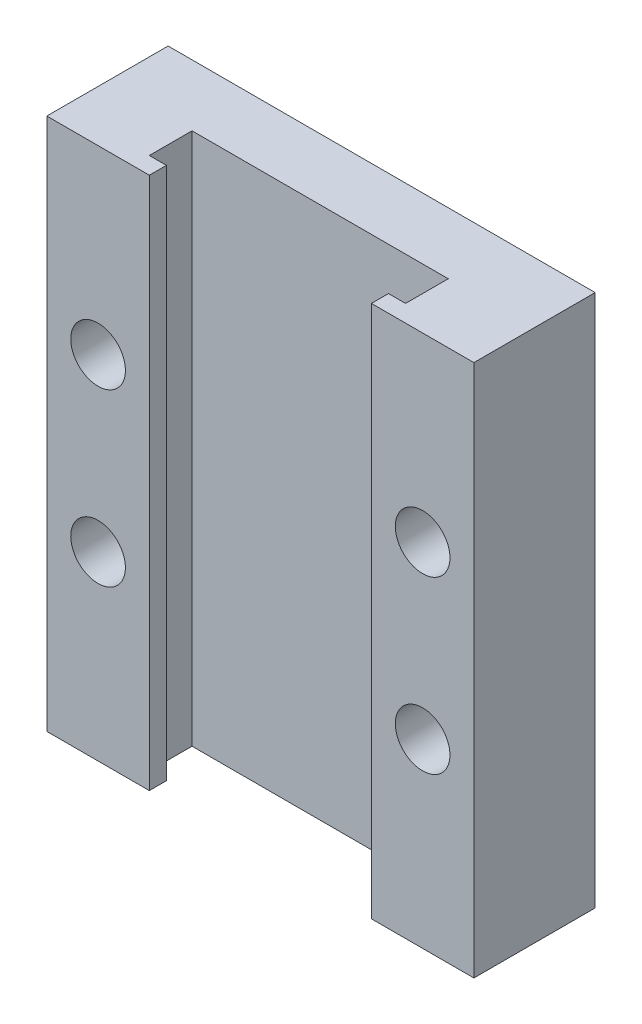
SolidWorks part; units mm, degrees
ref_plane "前视基准面" through (0, 0, 0) normal (0, 0, 1) x (1, 0, 0)
ref_plane "上视基准面" through (0, 0, 0) normal (0, 1, 0) x (1, 0, 0)
ref_plane "右视基准面" through (0, 0, 0) normal (1, 0, 0) x (0, 0, -1)
sketch "草图1" plane through (0, 0, 0) normal (0, 1, 0) x (1, 0, 0)
  line L0 (-7.5, -0.2751) -> (-6.5, -0.2751)
  line L1 (-6.5, -0.2751) -> (-6.5, -1.2751)
  line L2 (-6.5, -1.2751) -> (-12.5, -1.2751)
  line L3 (-12.5, -1.2751) -> (-12.5, 5.8249)
  line L4 (-12.5, 5.8249) -> (12.5, 5.8249)
  line L6 (7.5, 2.2249) -> (-7.5, 2.2249)
  line L7 (-7.5, 2.2249) -> (-7.5, -0.2751)
  line L8 (0, 5.8249) -> (0, -2.3974) construction
  line L9 (7.5, 2.2249) -> (7.5, -0.2751)
  line L10 (12.5, -1.2751) -> (12.5, 5.8249)
  line L11 (6.5, -1.2751) -> (12.5, -1.2751)
  line L12 (6.5, -0.2751) -> (6.5, -1.2751)
  line L13 (7.5, -0.2751) -> (6.5, -0.2751)
  point P12 (0, 2.2249)
  dimension "D1" = 7.1
  dimension "D2" = 25
  dimension "D3" = 1
  dimension "D4" = 1
  dimension "D5" = 2.5
  dimension "D6" = 7.5
extrude "凸台-拉伸1" add sketch "草图1" along normal blind 31.2
sketch "草图2" plane through (0, 0, -5.8249) normal (0, 0, -1) x (-1, 0, 0)
  line L0 (0, 31.2) -> (0, -6.1748) construction
  line L1 (-12.5, 31.2) -> (12.5, 31.2) construction
  line L2 (-12.5, 15.6) -> (19.4723, 15.6) construction
  line L3 (-12.5, 31.2) -> (-12.5, 0) construction
  circle A0 centre (-9.5, 20.6) radius 1.6
  circle A1 centre (9.5, 20.6) radius 1.6
  circle A2 centre (9.5, 10.6) radius 1.6
  circle A3 centre (-9.5, 10.6) radius 1.6
  dimension "D1" = 3.2
  dimension "D2" = 19
  dimension "D3" = 10
extrude "切除-拉伸1" cut sketch "草图2" against normal blind 10
